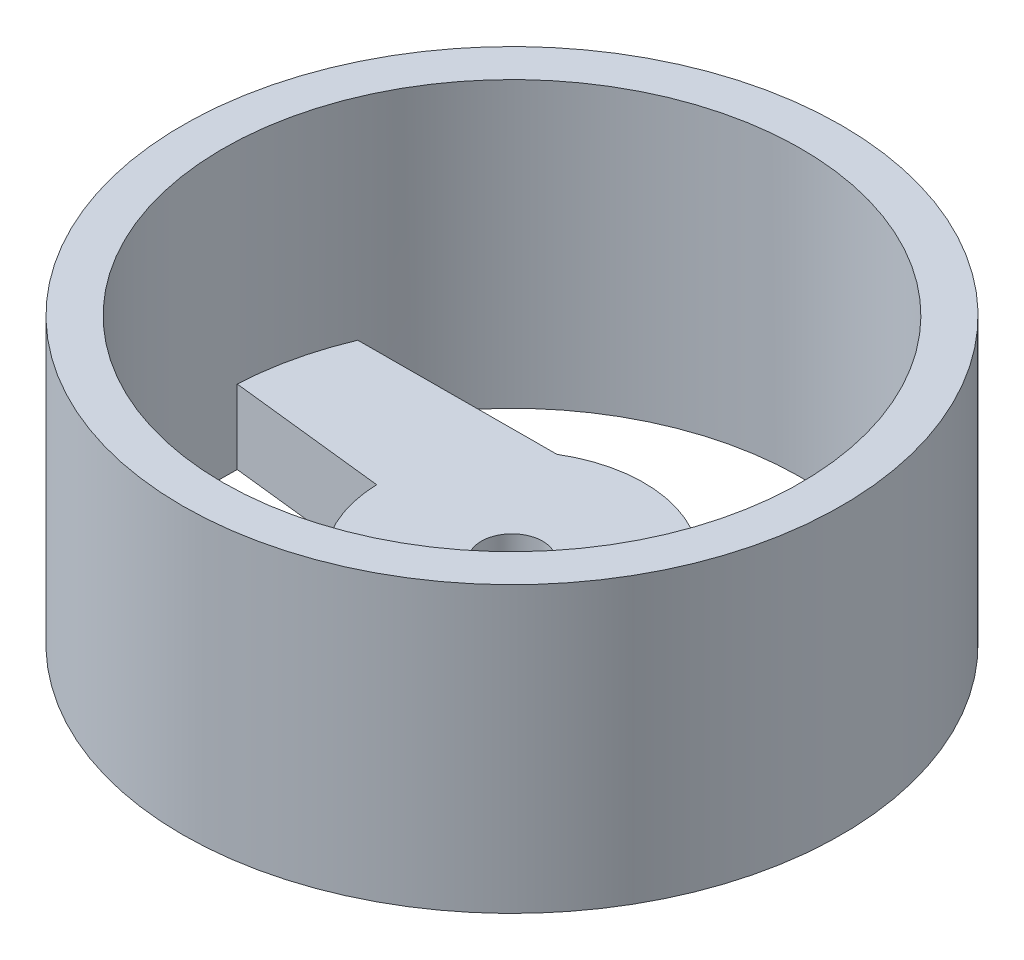
SolidWorks part; units mm, degrees
ref_plane "Alzado" through (0, 0, 0) normal (0, 0, 1) x (1, 0, 0)
ref_plane "Planta" through (0, 0, 0) normal (0, 1, 0) x (1, 0, 0)
ref_plane "Vista lateral" through (0, 0, 0) normal (1, 0, 0) x (0, 0, -1)
ref_plane "Plano1" through (0, 0, 0) normal (0, 0, -1) x (-1, 0, 0)
sketch "Croquis1" plane through (0, 0, 0) normal (0, 0, -1) x (-1, 0, 0)
  line L0 (-10.9509, 4) -> (0, 4)
  line L1 (0, 4) -> (0, 13.461)
  line L2 (0, 13.461) -> (-10.9509, 13.461)
  line L3 (-10.9509, 13.461) -> (-10.9509, 4)
  line L4 (0, 4) -> (0, 13.461) construction
revolve "Revolución1" add sketch "Croquis1" angle 360 about L4
sketch "Croquis2" plane through (0, 4, 0) normal (0, -1, 0) x (1, 0, 0)
  circle A0 centre (0, 0) radius 4
extrude "Saliente-Extruir1" add sketch "Croquis2" along normal blind 4
sketch "Croquis7" plane through (0, 4, 0) normal (0, -1, 0) x (1, 0, 0)
  line L0 (2.2904, 3.7377) -> (4.3947, 8.5438)
  line L1 (4.3829, -0.0807) -> (7.6571, -5.8034)
  arc A0 (4.3947, 8.5438) -> (7.6571, -5.8034) centre (0, 0) cw
  arc A1 (2.2904, 3.7377) -> (4.3829, -0.0807) centre (0, 0) cw
extrude "Cortar-Extruir1" cut sketch "Croquis7" against normal blind 10 contours L0 A0 L1 A1
pattern_circular "MatrizC1" count 3 over 360 about axis through (0, 0, 0) along (0, 1, 0) of "Cortar-Extruir1"
sketch "Croquis8" plane through (0, 13.461, 0) normal (0, 1, 0) x (1, 0, 0)
  circle A0 centre (0, 0) radius 9.6078
extrude "Cortar-Extruir2" cut sketch "Croquis8" against normal blind 7
sketch "Croquis9" plane through (0, 0, 0) normal (0, -1, 0) x (1, 0, 0)
  circle A0 centre (0, 0) radius 1.0197
extrude "Cortar-Extruir3" cut sketch "Croquis9" against normal through all
scale "Escala1" scale about centroid uniform scaling yes scale factor 0.565
